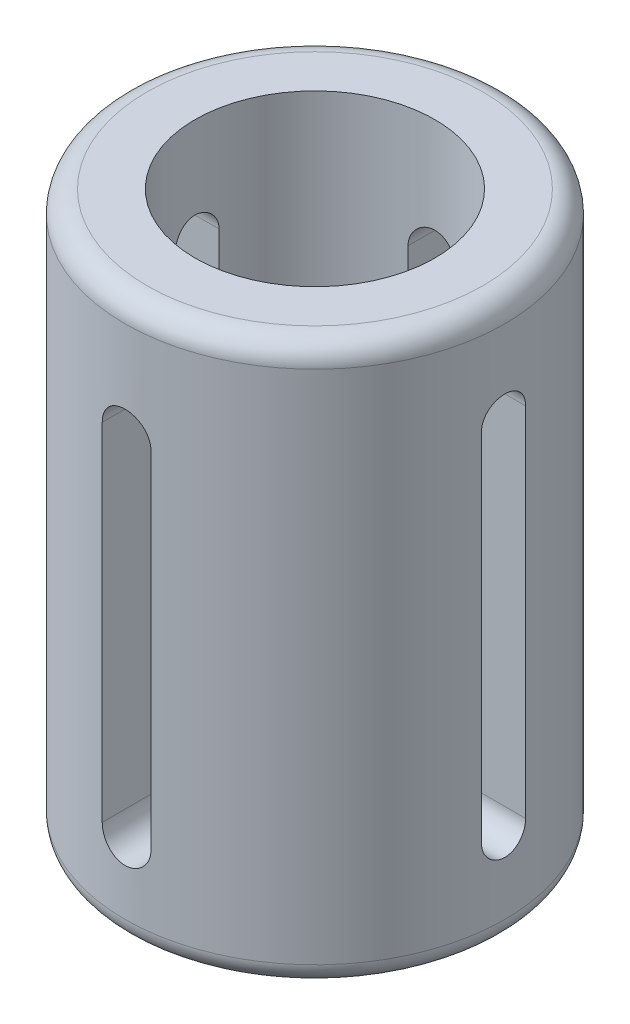
SolidWorks part; units mm, degrees
ref_plane "Спереди" through (0, 0, 0) normal (0, 0, 1) x (1, 0, 0)
ref_plane "Сверху" through (0, 0, 0) normal (0, 1, 0) x (1, 0, 0)
ref_plane "Справа" through (0, 0, 0) normal (1, 0, 0) x (0, 0, -1)
sketch "Эскиз1" plane through (0, 0, 0) normal (0, 1, 0) x (1, 0, 0)
  circle A0 centre (0, 0) radius 9.5
  circle A1 centre (0, 0) radius 6
  dimension "D1" = 19
  dimension "D2" = 12
extrude "Бобышка-Вытянуть1" add sketch "Эскиз1" along normal blind 28
fillet "Скругление1" radius 1.1 2 edges at (0, 0, 9.5) (0, 28, 9.5)
sketch "Эскиз2" plane through (0, 0, 0) normal (0, 0, 1) x (1, 0, 0)
  line L0 (0, 28) -> (0, 0) construction
  line L1 (6, 28) -> (-6, 28) construction
  line L2 (0, 21.9876) -> (0, 4.6586) construction
  line L3 (1.2184, 21.9876) -> (1.2184, 4.6586)
  line L4 (-1.2184, 21.9876) -> (-1.2184, 4.6586)
  arc A0 (1.2184, 21.9876) -> (-1.2184, 21.9876) centre (0, 21.9876) ccw
  arc A1 (-1.2184, 4.6586) -> (1.2184, 4.6586) centre (0, 4.6586) ccw
  point P7 (0, 13.3231)
extrude "Вырез-Вытянуть1" cut sketch "Эскиз2" against normal blind 17 and the other way blind 15
sketch "Эскиз3" plane through (0, 0, 0) normal (1, 0, 0) x (0, 0, -1)
  line L0 (0, 26.9) -> (0, 0) construction
  line L1 (-9.5, 26.9) -> (9.5, 26.9) construction
  line L2 (0, 22.7612) -> (0, 4.8907) construction
  line L3 (1.1024, 22.7612) -> (1.1024, 4.8907)
  line L4 (-1.1024, 22.7612) -> (-1.1024, 4.8907)
  arc A0 (1.1024, 22.7612) -> (-1.1024, 22.7612) centre (0, 22.7612) ccw
  arc A1 (-1.1024, 4.8907) -> (1.1024, 4.8907) centre (0, 4.8907) ccw
  point P7 (0, 13.8259)
extrude "Вырез-Вытянуть2" cut sketch "Эскиз3" against normal blind 17 and the other way blind 17
